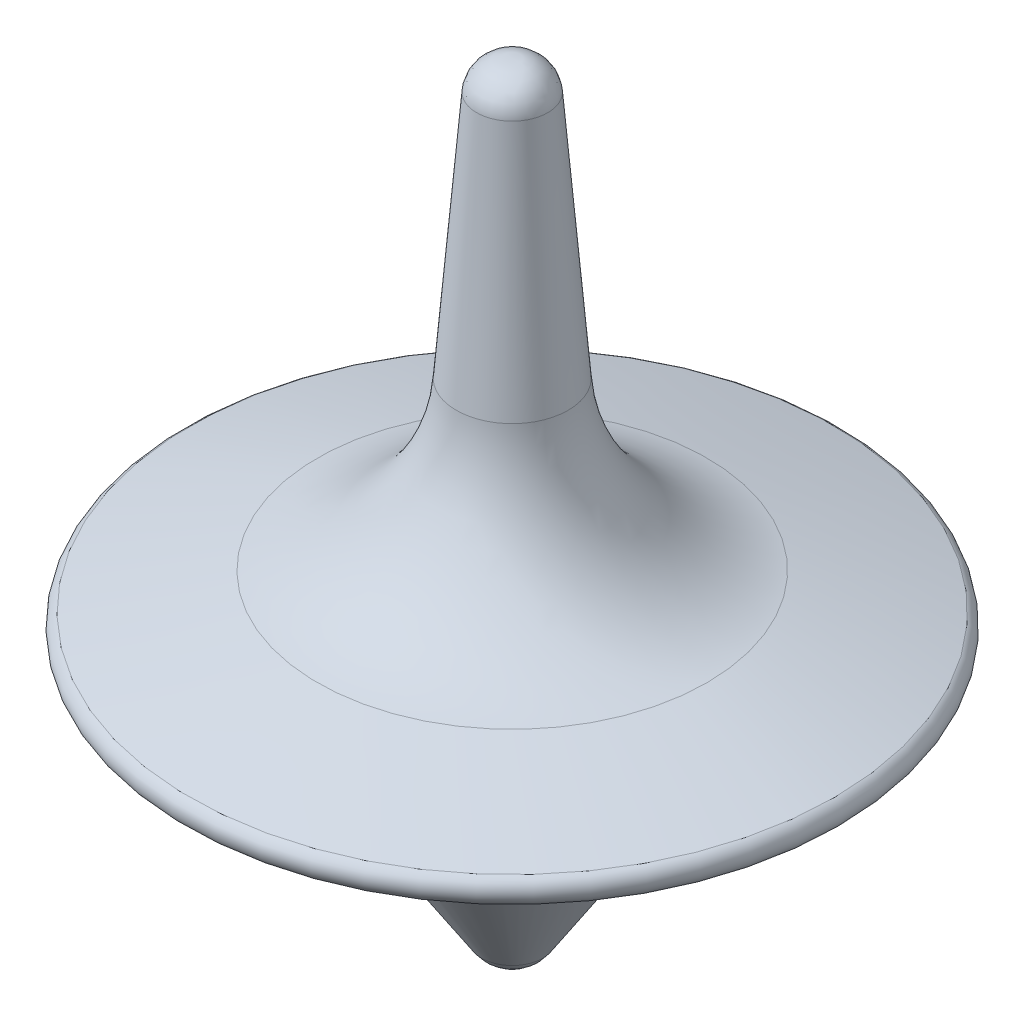
SolidWorks part; units mm, degrees
ref_plane "Plano frontal" through (0, 0, 0) normal (0, 0, 1) x (1, 0, 0)
ref_plane "Plano superior" through (0, 0, 0) normal (0, 1, 0) x (1, 0, 0)
ref_plane "Plano direito" through (0, 0, 0) normal (1, 0, 0) x (0, 0, -1)
other "Centro da massa"
sketch "Esboço1" plane through (0, 0, 0) normal (0, 0, 1) x (1, 0, 0)
  line L0 (1.0166, -17.5343) -> (1.0166, 16.2657)
  arc A0 (6.4866, -10.3443) -> (2.3366, -16.7543) centre (-62.6663, 29.8786) cw
  arc A1 (2.3366, -16.7543) -> (1.0166, -17.5343) centre (0.8989, -15.8283) cw
  arc A2 (6.4866, -10.3443) -> (10.6216, -7.0743) centre (13.2393, -14.6339) cw
  arc A3 (10.6216, -7.0743) -> (14.7216, -5.6243) centre (32.6637, -62.8788) cw
  arc A4 (14.7216, -5.6243) -> (14.9336, -4.4432) centre (14.6385, -4.9998) ccw
  arc A5 (9.4336, -2.8932) -> (14.9336, -4.4432) centre (-22.4467, -126.5497) cw
  arc A6 (9.4336, -2.8932) -> (3.4336, 4.3068) centre (11.4146, 4.8577) cw
  arc A7 (3.4336, 4.3068) -> (2.5536, 15.0068) centre (222.188, 27.684) cw
  arc A8 (1.0166, 16.2657) -> (2.5536, 15.0068) centre (1.2058, 14.929) cw
  dimension "D4" = 4.135
  dimension "D6" = 127.7
  dimension "D9" = 1.32
  dimension "D10" = 3.27
  dimension "D11" = 1.2
  dimension "D7" = 1.45
  dimension "D12" = 0.63
  dimension "D13" = 1.55
  dimension "D15" = 6
  dimension "D20" = 0.88
  dimension "D21" = 1.35
  dimension "D22" = 0.78
  dimension "D19" = 10.7
  dimension "D25" = 1.71
  dimension "D26" = 80
  dimension "D27" = 8
  dimension "D17" = 8
  dimension "D28" = 220
  dimension "D29" = 60
  dimension "D3" = 6.41
  dimension "D5" = 4.1
  dimension "D8" = 4.15
  dimension "D14" = 7.2
  dimension "D16" = 5.5
  dimension "D18" = 33.8
revolve "Revolução1" add sketch "Esboço1" angle 360 about L0
